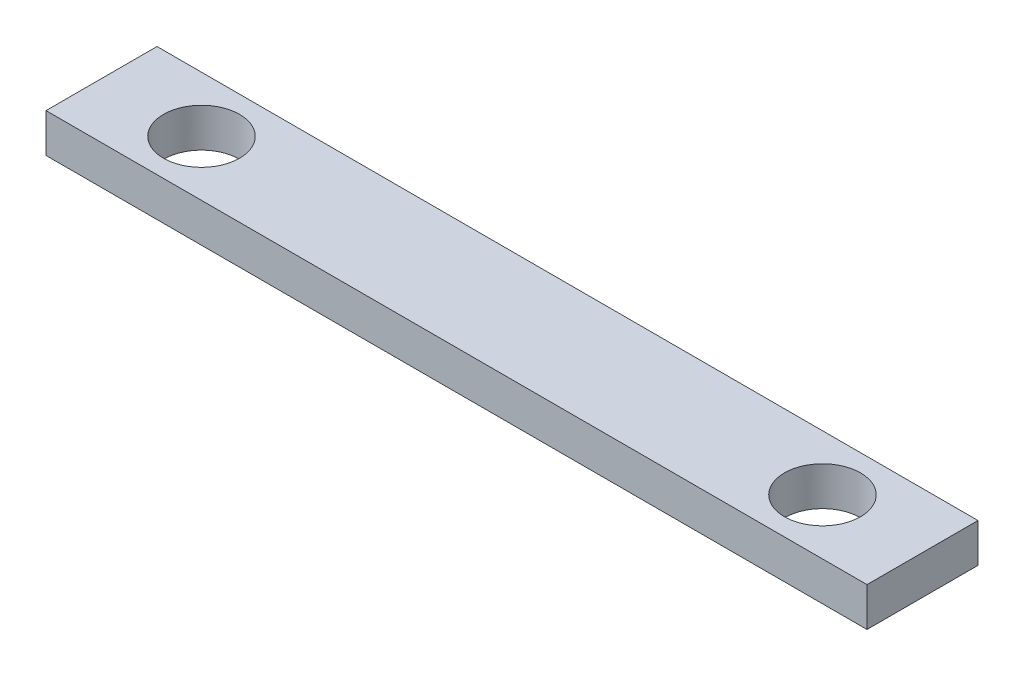
SolidWorks part; units mm, degrees
ref_plane "Front Plane" through (0, 0, 0) normal (0, 0, 1) x (1, 0, 0)
ref_plane "Top Plane" through (0, 0, 0) normal (0, 1, 0) x (1, 0, 0)
ref_plane "Right Plane" through (0, 0, 0) normal (1, 0, 0) x (0, 0, -1)
sketch "Sketch1" plane through (0, 0, 0) normal (0, 0, 1) x (1, 0, 0)
  line L0 (0, 0) -> (54.0258, 0)
  line L1 (54.0258, 0) -> (54.0258, 3.9878)
  line L2 (54.0258, 3.9878) -> (51.1766, 11.0383)
  line L3 (51.0286, 11.7997) -> (51.0286, 15.113)
  line L4 (11.2776, 16.383) -> (10.0076, 15.113)
  line L5 (49.7586, 16.383) -> (11.2776, 16.383)
  line L6 (51.0286, 15.113) -> (49.7586, 16.383)
  line L7 (10.0076, 15.113) -> (10.0076, 12.4279)
  line L8 (9.1855, 10.7953) -> (0, 3.9878)
  line L9 (0, 3.9878) -> (0, 0)
  arc A0 (51.1766, 11.0383) -> (51.0286, 11.7997) centre (53.0606, 11.7997) cw
  arc A1 (10.0076, 12.4279) -> (9.1855, 10.7953) centre (7.9756, 12.4279) cw
  point P8 (51.0286, 16.383)
  point P12 (10.0076, 16.383)
  point P16 (51.0286, 11.4046)
  dimension "D8" = 2.032
  dimension "D1" = 54.0258
  dimension "D2" = 16.383
  dimension "D3" = 41.021
  dimension "D4" = 3.9878
  dimension "D5" = 3.9878
  dimension "D6" = 2.9972
  dimension "D7" = 4.9784
extrude "Boss-Extrude1" add sketch "Sketch1" against normal blind 25.654
sketch "Sketch2" plane through (54.0258, 0, 0) normal (1, 0, 0) x (0, 0, -1)
  line L0 (25.654, 3.9878) -> (0, 3.9878) construction
  line L1 (25.654, 3.9878) -> (5.0038, 3.9878)
  line L2 (5.0038, 16.383) -> (5.0038, 3.9878)
  line L3 (0, 3.9878) -> (0, 11.0383) construction
  line L4 (25.654, 16.383) -> (0, 16.383) construction
  line L5 (25.654, 16.383) -> (5.0038, 16.383)
  line L6 (25.654, 11.7997) -> (25.654, 15.113) construction
  line L7 (25.654, 3.9878) -> (25.654, 16.383)
  dimension "D1" = 5.0038
extrude "Cut-Extrude1" cut sketch "Sketch2" against normal through all
sketch "Sketch3" plane through (0, 3.9878, 0) normal (0, 1, 0) x (1, 0, 0)
  line L0 (5.9944, 25.654) -> (5.9944, 5.0038)
  line L1 (48.0314, 5.0038) -> (48.0314, 25.654)
  line L4 (54.0258, 5.0038) -> (54.0258, 25.654)
  line L5 (54.0258, 25.654) -> (0, 25.654)
  line L6 (0, 25.654) -> (0, 5.0038)
  line L7 (0, 5.0038) -> (54.0258, 5.0038)
  line L8 (54.0258, 5.0038) -> (54.0258, 25.654) construction
  line L9 (48.0314, 25.654) -> (5.9944, 25.654)
  line L10 (0, 25.654) -> (0, 5.0038) construction
  line L11 (5.9944, 5.0038) -> (48.0314, 5.0038)
  dimension "D1" = 0
  dimension "D2" = 5.9944
extrude "Cut-Extrude2" cut sketch "Sketch3" against normal through all
sketch "Sketch4" plane through (0, 0, 0) normal (0, 0, 1) x (1, 0, 0)
  line L2 (0, 3.937) -> (54.0258, 3.937)
  line L3 (6.902, 3.937) -> (10.414, 3.937)
  line L5 (49.7586, 13.9446) -> (11.2776, 13.9446)
  line L6 (47.752, 13.9446) -> (42.6212, 13.9446)
  line L8 (49.2506, 11.7997) -> (49.2506, 15.113)
  line L9 (49.2506, 5.4356) -> (49.2506, 12.446)
  line L11 (13.3096, 15.113) -> (13.3096, 12.4279)
  line L12 (13.3096, 12.446) -> (13.3096, 5.4356)
  line L13 (11.9126, 8.0384) -> (11.9126, 5.4356)
  line L14 (10.0476, 9.6321) -> (0.8621, 2.8246)
  line L15 (9.5217, 9.2424) -> (6.0097, 6.6396)
  line L16 (11.9126, 13.9446) -> (11.9126, 3.937) construction
  line L17 (21.4376, 12.446) -> (21.4376, 5.4356)
  line L18 (22.8346, 12.446) -> (22.8346, 5.4356)
  line L19 (41.1226, 5.4356) -> (41.1226, 12.446)
  line L20 (39.7256, 5.4356) -> (39.7256, 12.446)
  line L21 (14.8082, 3.937) -> (19.939, 3.937)
  line L22 (24.3332, 3.937) -> (38.227, 3.937)
  line L23 (42.6212, 3.937) -> (47.752, 3.937)
  line L24 (38.227, 13.9446) -> (24.3332, 13.9446)
  line L25 (19.939, 13.9446) -> (14.8082, 13.9446)
  line L26 (49.2506, 3.937) -> (49.2506, 13.9446) construction
  line L27 (41.1226, 3.937) -> (41.1226, 13.9446) construction
  line L28 (22.8346, 13.9446) -> (22.8346, 3.937) construction
  line L29 (39.7256, 3.937) -> (39.7256, 13.9446) construction
  line L30 (13.3096, 13.9446) -> (13.3096, 3.937) construction
  line L31 (21.4376, 13.9446) -> (21.4376, 3.937) construction
  arc A0 (47.752, 13.9446) -> (49.2506, 12.446) centre (47.752, 12.446) cw
  arc A1 (49.2506, 5.4356) -> (47.752, 3.937) centre (47.752, 5.4356) cw
  arc A2 (42.6212, 3.937) -> (41.1226, 5.4356) centre (42.6212, 5.4356) cw
  arc A3 (41.1226, 12.446) -> (42.6212, 13.9446) centre (42.6212, 12.446) cw
  arc A4 (22.8346, 12.446) -> (24.3332, 13.9446) centre (24.3332, 12.446) cw
  arc A5 (38.227, 13.9446) -> (39.7256, 12.446) centre (38.227, 12.446) cw
  arc A6 (39.7256, 5.4356) -> (38.227, 3.937) centre (38.227, 5.4356) cw
  arc A7 (24.3332, 3.937) -> (22.8346, 5.4356) centre (24.3332, 5.4356) cw
  arc A8 (13.3096, 5.4356) -> (14.8082, 3.937) centre (14.8082, 5.4356) ccw
  arc A9 (19.939, 3.937) -> (21.4376, 5.4356) centre (19.939, 5.4356) ccw
  arc A10 (21.4376, 12.446) -> (19.939, 13.9446) centre (19.939, 12.446) ccw
  arc A11 (14.8082, 13.9446) -> (13.3096, 12.446) centre (14.8082, 12.446) ccw
  arc A12 (9.5217, 9.2424) -> (11.9126, 8.0384) centre (10.414, 8.0384) cw
  arc A13 (11.9126, 5.4356) -> (10.414, 3.937) centre (10.414, 5.4356) cw
  arc A14 (6.902, 3.937) -> (6.0097, 6.6396) centre (6.902, 5.4356) cw
  dimension "D11" = 1.4986
  dimension "D1" = 3.937
  dimension "D2" = 2.4384
  dimension "D3" = 1.778
  dimension "D4" = 3.302
  dimension "D5" = 1.4478
  dimension "D6" = 1.397
  dimension "D7" = 8.128
  dimension "D8" = 1.397
  dimension "D9" = 8.128
  dimension "D10" = 1.397
extrude "Cut-Extrude3" cut sketch "Sketch4" against normal blind 5.08
sketch "Sketch5" plane through (0, 3.9878, 0) normal (0, 1, 0) x (1, 0, 0)
  line L0 (48.0314, 25.654) -> (54.0258, 25.654) construction
  line L1 (48.0314, 25.654) -> (54.0258, 25.654) construction
  line L2 (5.9944, 25.654) -> (48.0314, 25.654) construction
  line L3 (27.0129, 25.654) -> (27.0129, 11.3538) construction
  circle A0 centre (51.0286, 21.336) radius 1.0795
  circle A1 centre (51.0286, 11.3538) radius 1.0795
  circle A2 centre (2.9972, 11.3538) radius 1.0795
  circle A3 centre (2.9972, 21.336) radius 1.0795
  point P6 (51.0286, 25.654)
  point P7 (51.0286, 25.654)
  dimension "D1" = 2.159
  dimension "D2" = 2.159
  dimension "D3" = 4.318
  dimension "D4" = 0
  dimension "D5" = 0
  dimension "D6" = 9.9822
extrude "Cut-Extrude4" cut sketch "Sketch5" against normal through all
sketch "Sketch6" plane through (0, 0, 0) normal (0, -1, 0) x (1, 0, 0)
  line L0 (27.0129, 0) -> (27.0129, -5.0038) construction
  line L1 (0, 0) -> (54.0258, 0) construction
  line L2 (5.9944, -5.0038) -> (48.0314, -5.0038) construction
  line L3 (27.0129, -2.5019) -> (56.1106, -2.5019) construction
  line L4 (27.0129, -2.5019) -> (-2.3785, -2.5019) construction
  line L5 (54.0258, -25.654) -> (54.0258, 0) construction
  circle A0 centre (45.2501, -2.5019) radius 1.7145
  circle A1 centre (17.2593, -2.5019) radius 1.7145
  dimension "D1" = 3.429
  dimension "D2" = 3.429
  dimension "D3" = 8.7757
  dimension "D4" = 27.9908
extrude "Cut-Extrude5" cut sketch "Sketch6" against normal through all
sketch "Sketch7" plane through (0, 16.383, 0) normal (0, 1, 0) x (1, 0, 0)
  line L0 (-1.922, 27.3092) -> (11.2776, 27.3092)
  line L1 (49.7586, 27.3092) -> (59.2445, 27.3092)
  line L2 (59.2445, 27.3092) -> (59.2445, -1.0664)
  line L3 (59.2445, -1.0664) -> (49.7586, -1.0664)
  line L4 (49.7586, 5.0038) -> (11.2776, 5.0038)
  line L5 (11.2776, 5.0038) -> (11.2776, 0)
  line L6 (11.2776, 0) -> (49.7586, 0)
  line L7 (49.7586, 0) -> (49.7586, 5.0038)
  line L9 (11.2776, 27.3092) -> (11.2776, -1.0664)
  line L11 (49.7586, -1.0664) -> (49.7586, 27.3092)
  line L12 (-1.922, -1.0664) -> (-1.922, 27.3092)
  line L13 (11.2776, -1.0664) -> (-1.922, -1.0664)
  dimension "D1" = 0
extrude "Cut-Extrude6" cut sketch "Sketch7" against normal through all
sketch "Sketch8" plane through (0, 0, 0) normal (0, 0, 1) x (1, 0, 0)
  line L1 (11.2776, 16.383) -> (11.2776, 9.2632) construction
  line L2 (49.7586, 14.6304) -> (11.2776, 14.6304)
  line L3 (49.7586, 14.6304) -> (11.2776, 14.6304)
  line L4 (11.2776, 14.6304) -> (11.2776, 0)
  line L5 (11.2776, 0) -> (49.7586, 0) construction
  line L6 (11.2776, 0) -> (49.7586, 0)
  line L7 (49.7586, 0) -> (49.7586, 16.383) construction
  line L8 (49.7586, 0) -> (49.7586, 14.6304)
  dimension "D1" = 1.7526
extrude "Cut-Extrude7" cut sketch "Sketch8" against normal through all
sketch "Sketch9" plane through (0, 16.383, 0) normal (0, 1, 0) x (1, 0, 0)
  line L0 (17.2593, 2.5019) -> (45.2501, 2.5019) construction
  line L1 (31.2547, 2.5019) -> (31.2547, 7.0096) construction
  line L2 (49.7586, 5.0038) -> (49.7586, 0) construction
  line L3 (49.7586, 5.0038) -> (49.7586, 0) construction
  line L4 (12.7508, 5.0038) -> (12.7508, 0)
  line L5 (11.2776, 5.0038) -> (11.2776, 0) construction
  line L6 (11.2776, 5.0038) -> (11.2776, 0)
  line L7 (11.2776, 5.0038) -> (49.7586, 5.0038) construction
  line L8 (11.2776, 5.0038) -> (12.7508, 5.0038)
  line L9 (49.7586, 0) -> (11.2776, 0) construction
  line L10 (12.7508, 0) -> (11.2776, 0)
  circle A0 centre (17.2593, 2.5019) radius 1.7145 construction
  circle A1 centre (17.2593, 2.5019) radius 1.7145 construction
  circle A2 centre (45.2501, 2.5019) radius 1.7145 construction
  circle A3 centre (45.2501, 2.5019) radius 1.7145 construction
extrude "Cut-Extrude8" cut sketch "Sketch9" against normal blind 2.54
